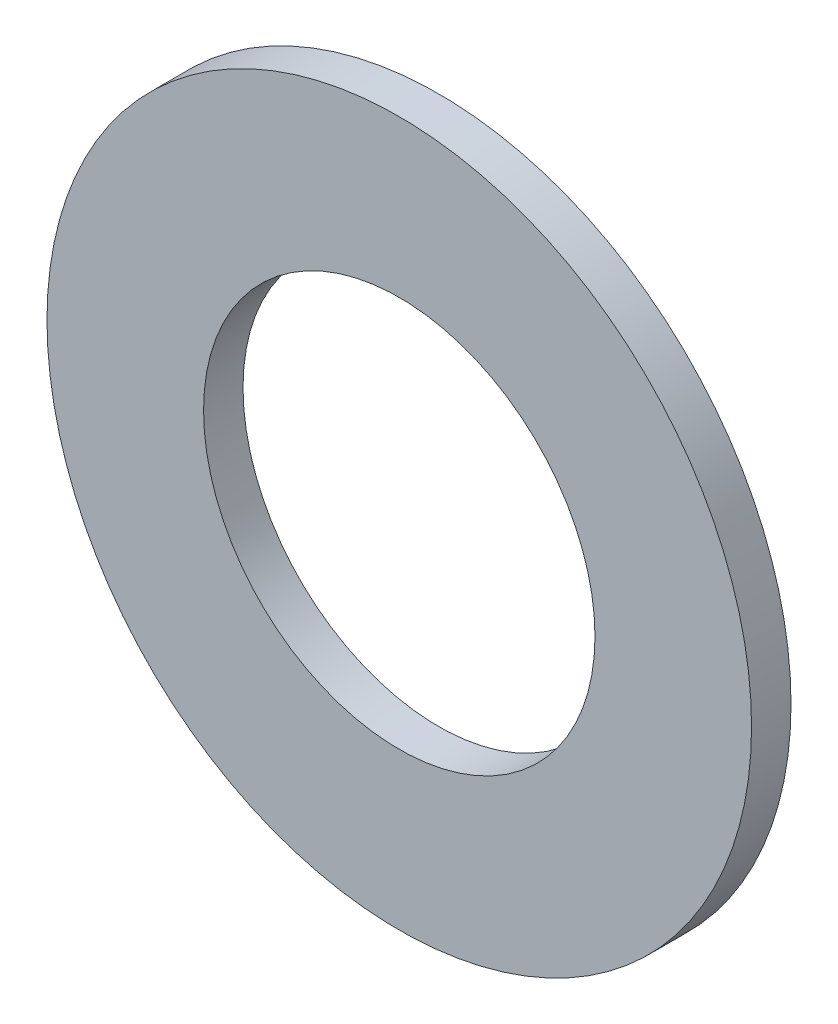
SolidWorks part; units mm, degrees
ref_plane "Front Plane" through (0, 0, 0) normal (0, 0, 1) x (1, 0, 0)
ref_plane "Top Plane" through (0, 0, 0) normal (0, 1, 0) x (1, 0, 0)
ref_plane "Right Plane" through (0, 0, 0) normal (1, 0, 0) x (0, 0, -1)
sketch "Sketch1" plane through (0, 0, 0) normal (0, 0, 1) x (1, 0, 0)
  line L0 (-7.9375, 0) -> (7.9375, 0) construction
  circle A0 centre (0, 0) radius 14.2875 construction
  circle A1 centre (0, 0) radius 7.9375 construction
  dimension "OD" = 28.575
  dimension "ID" = 15.875
  dimension "For Shaft Diameter" = 15.875
sketch "Sketch2" plane through (0, 0, 0) normal (1, 0, 0) x (0, 0, -1)
  line L4 (0.8001, 14.2875) -> (-0.8001, 14.2875) construction
  point P0 (0, 14.2875)
  dimension "Thickness" = 1.6002
sketch "Sketch3" plane through (0, 0, 0) normal (0, 0, 1) x (1, 0, 0)
  circle A0 centre (0, 0) radius 7.9375 construction
  circle A1 centre (0, 0) radius 14.2875 construction
  circle A3 centre (0, 0) radius 7.9375
  circle A5 centre (0, 0) radius 14.2875
extrude "Boss-Extrude1" add sketch "Sketch3" against normal up to vertex (0.8001 mm away) and the other way up to vertex (0.8001 mm away)
equation "\"D1\"= \"Thickness@Sketch2\""
